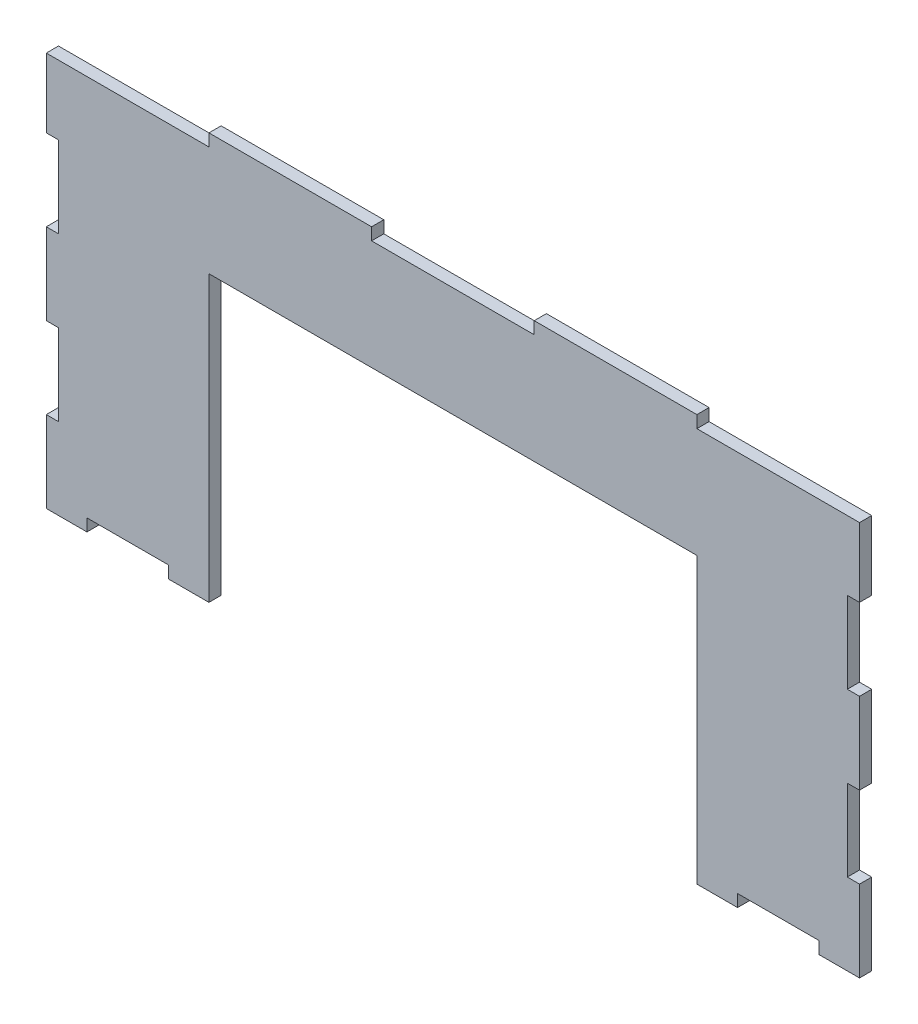
SolidWorks part; units mm, degrees
ref_plane "Alzado" through (0, 0, 0) normal (0, 0, 1) x (1, 0, 0)
ref_plane "Planta" through (0, 0, 0) normal (0, 1, 0) x (1, 0, 0)
ref_plane "Vista lateral" through (0, 0, 0) normal (1, 0, 0) x (0, 0, -1)
sketch "Sketch1" plane through (0, 0, 0) normal (0, 0, 1) x (1, 0, 0)
  line L0 (-60, 5.0977) -> (-60, -50)
  line L1 (-100, 50) -> (100, 50)
  line L2 (-100, 50) -> (-100, -50)
  line L3 (-100, -50) -> (-90, -50)
  line L4 (100, 50) -> (100, -50)
  line L5 (-100, 50) -> (-40, 20) construction
  line L6 (-100, -50) -> (-60, -30) construction
  line L7 (-60, 20) -> (60, 20)
  line L8 (-60, 20) -> (-60, 5.0977)
  line L10 (60, 20) -> (60, -40.1784)
  line L12 (-90, -50) -> (-90, -47)
  line L13 (60, -40.1784) -> (60, -50)
  line L14 (60, -50) -> (70, -50)
  line L15 (-90, -47) -> (-70, -47)
  line L16 (40, 20) -> (100, 50) construction
  line L17 (60, -30) -> (100, -50) construction
  line L18 (-70, -47) -> (-70, -50)
  line L19 (-70, -50) -> (-60, -50)
  line L20 (0, 0) -> (0, -20.1087) construction
  line L21 (70, -47) -> (70, -50)
  line L22 (90, -47) -> (70, -47)
  line L23 (90, -50) -> (90, -47)
  line L25 (90, -50) -> (100, -50)
  point P0 (0, 0)
  point P6 (0, 0)
  dimension "D1" = 200
  dimension "D2" = 100
  dimension "D3" = 120
  dimension "D4" = 40
  dimension "D5" = 10
  dimension "D6" = 30
  dimension "D7" = 20
  dimension "D8" = 3
extrude "Boss-Extrude1" add sketch "Sketch1" along normal blind 3
sketch "Sketch2" plane through (0, 0, 3) normal (0, 0, 1) x (1, 0, 0)
  line L0 (-100, 50) -> (-100, 30) construction
  line L1 (-100, 50) -> (-100, -50) construction
  line L2 (-100, 30) -> (-97, 30)
  line L3 (-97, 30) -> (-97, 10)
  line L4 (-97, 10) -> (-100, 10)
  line L5 (100, 50) -> (-100, 50) construction
  line L6 (-100, 10) -> (-100, -10)
  line L7 (-100, -10) -> (-97, -10)
  line L8 (-97, -10) -> (-97, -30)
  line L9 (-97, -30) -> (-100, -30)
  line L10 (0, 0) -> (0, -30) construction
  line L11 (97, -30) -> (100, -30)
  line L12 (97, -10) -> (97, -30)
  line L13 (100, -10) -> (97, -10)
  line L14 (97, 10) -> (100, 10)
  line L15 (100, 30) -> (97, 30)
  line L16 (97, 30) -> (97, 10)
  line L17 (-100, 50) -> (-60, 50)
  line L18 (-60, 50) -> (-20, 50)
  line L19 (-100, 50) -> (-100, 47)
  line L20 (20, 50) -> (60, 50)
  line L21 (-60, 50) -> (-60, 47)
  line L22 (-60, 47) -> (-100, 47)
  line L23 (-20, 50) -> (-20, 47)
  line L24 (-20, 47) -> (20, 47)
  line L25 (20, 47) -> (20, 50)
  line L26 (60, 50) -> (60, 47)
  line L27 (60, 47) -> (100, 47)
  line L28 (100, -50) -> (100, 50) construction
  line L29 (-20, 50) -> (20, 50)
  line L30 (60, 50) -> (100, 50)
  line L31 (100, 50) -> (100, 47)
  line L32 (-100, 10) -> (-100, 30)
  line L33 (-100, -10) -> (-100, -30)
  line L34 (100, -30) -> (100, -10)
  line L35 (100, 10) -> (100, 30)
  line L36 (-20, 50) -> (20, 50)
  line M16 (100, -50) -> (100, 50)
  line M17 (100, 50) -> (-100, 50)
  line M18 (-100, 50) -> (-100, -50)
  dimension "D1" = 20
  dimension "D2" = 20
  dimension "D3" = 20
  dimension "D4" = 3
  dimension "D5" = 20
  dimension "D6" = 40
  dimension "D7" = 40
  dimension "D8" = 40
  dimension "D9" = 40
  dimension "D10" = 3
  dimension "D11" = 3
  dimension "D12" = 3
extrude "Cut-Extrude1" cut sketch "Sketch2" against normal blind 3 contours L9 L8 L7 M18 | L4 L3 L2 M18 | L24 L25 L23 M17 | L26 L27 M16 M17 | L15 L16 L14 M16 | L13 L12 L11 M16 | L21 L22 L19 L17
